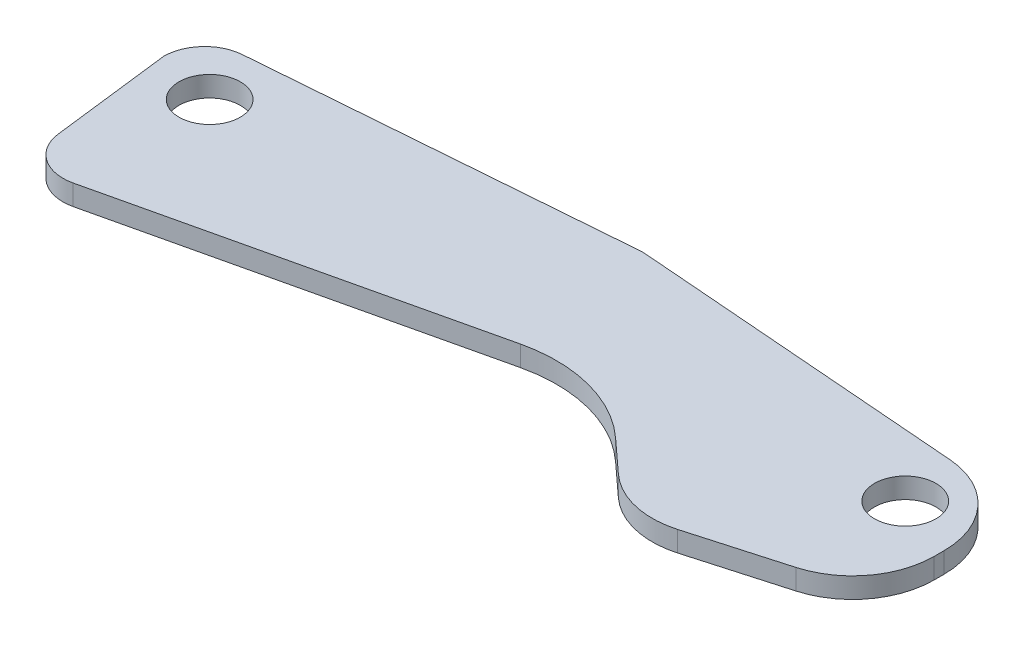
SolidWorks part; units mm, degrees
material "1060 Alloy"
ref_plane "Front Plane" through (0, 0, 0) normal (0, 0, 1) x (1, 0, 0)
ref_plane "Top Plane" through (0, 0, 0) normal (0, 1, 0) x (1, 0, 0)
ref_plane "Right Plane" through (0, 0, 0) normal (1, 0, 0) x (0, 0, -1)
sketch "Sketch1" plane through (0, 0, 0) normal (0, 1, 0) x (1, 0, 0)
  line L1 (-20, -5.75) -> (20, -5.75)
  line L2 (-20, -5.75) -> (-20, 5.75)
  line L3 (-20, 5.75) -> (20, 5.75)
  line L4 (20, -5.75) -> (20, 5.75)
  line L5 (-20, -5.75) -> (20, 5.75) construction
  line L6 (-20, 5.75) -> (20, -5.75) construction
  point P0 (0, 0)
  dimension "D1" = 40
  dimension "D2" = 11.5
extrude "Boss-Extrude1" add sketch "Sketch1" along normal blind 1
sketch "Sketch2" plane through (0, 1, 0) normal (0, 1, 0) x (1, 0, 0)
  line L0 (0, 5.75) -> (20, 4.1779)
  line L1 (20, 5.75) -> (-20, 5.75) construction
  line L2 (20, -5.75) -> (20, 5.75) construction
  line L3 (0, 5.75) -> (-20, 4.1779)
  line L4 (-20, 5.75) -> (-20, -5.75) construction
  line L5 (0, 5.75) -> (-20, 5.75)
  line L6 (-20, 5.75) -> (-20, 4.1779)
  line L7 (20, 4.1779) -> (20, 5.75)
  line L8 (20, 5.75) -> (0, 5.75)
  line M3 (20, -5.75) -> (20, 5.75)
  line M4 (20, 5.75) -> (-20, 5.75)
  line M5 (-20, 5.75) -> (-20, -5.75)
extrude "Cut-Extrude1" cut sketch "Sketch2" against normal blind 1 contours L3 M4 M5 | L0 M4 M3
fillet "Fillet1" radius 2 1 edges at (0, 0.5, -5.75)
fillet "Fillet2" radius 4 1 edges at (20, 0.5, -4.1779)
fillet "Fillet3" radius 2 1 edges at (-20, 0.5, -4.1779)
sketch "Sketch3" plane through (0, 1, 0) normal (0, 1, 0) x (1, 0, 0)
  line L0 (-20, 2.3289) -> (-19.0161, -5.75)
  line L1 (-20, -5.75) -> (20, -5.75) construction
  line L2 (-19.0161, -5.75) -> (-20, -5.75)
  line L3 (-20, -5.75) -> (-20, 2.3289)
extrude "Cut-Extrude2" cut sketch "Sketch3" against normal blind 1
sketch "Sketch4" plane through (0, 1, 0) normal (0, 1, 0) x (1, 0, 0)
  line L0 (-19.0161, -5.75) -> (4.4878, -0.2996)
  line L1 (4.4878, -0.2996) -> (10.4447, -5.75)
  line L2 (-19.0161, -5.75) -> (20, -5.75) construction
  line L3 (10.4447, -5.75) -> (20, -3.0248)
  line L4 (20, -5.75) -> (20, 0.48) construction
  line L5 (-19.0161, -5.75) -> (20, -5.75)
  line L6 (20, -5.75) -> (20, -3.0248)
  line M3 (-19.0161, -5.75) -> (20, -5.75)
  line M4 (20, -5.75) -> (20, 0.48)
extrude "Cut-Extrude3" cut sketch "Sketch4" against normal blind 1 contours L1 L0 M3 | L3 M3 M4
fillet "Fillet4" radius 2 1 edges at (-19.0161, 0.5, 5.75)
fillet "Fillet5" radius 7 1 edges at (4.4878, 0.5, 0.2996)
fillet "Fillet6" radius 4 1 edges at (10.4447, 0.5, 5.75)
fillet "Fillet7" radius 4 1 edges at (20, 0.5, 3.0248)
sketch "Sketch5" plane through (0, 1, 0) normal (0, 1, 0) x (1, 0, 0)
  circle A1 centre (-17.0484, 1.6241) radius 1.5
  circle A2 centre (16.9516, 1.6241) radius 1.5015
  point P0 (-17.0484, 1.6241)
  point P1 (16.9516, 1.6241)
  dimension "D2" = 3
  dimension "D1" = 34
extrude "Cut-Extrude4" cut sketch "Sketch5" against normal blind 1
